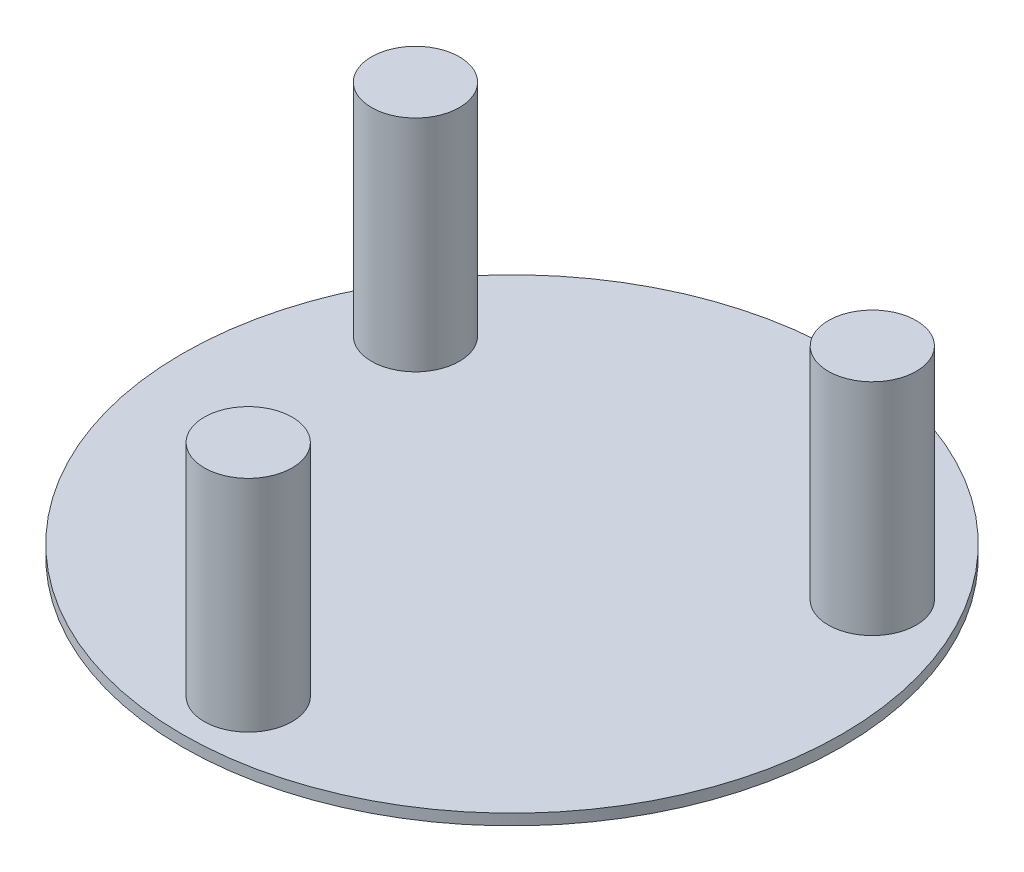
SolidWorks part; units mm, degrees
ref_plane "前视基准面" through (0, 0, 0) normal (0, 0, 1) x (1, 0, 0)
ref_plane "上视基准面" through (0, 0, 0) normal (0, 1, 0) x (1, 0, 0)
ref_plane "右视基准面" through (0, 0, 0) normal (1, 0, 0) x (0, 0, -1)
sketch "草图1" plane through (0, 0, 0) normal (0, 1, 0) x (1, 0, 0)
  circle A0 centre (0, 0) radius 150
  dimension "D1" = 300
extrude "凸台-拉伸1" add sketch "草图1" along normal blind 5
sketch "草图2" plane through (0, 5, 0) normal (0, 1, 0) x (1, 0, 0)
  circle A0 centre (0, 0) radius 120 construction
  circle A1 centre (0, -120) radius 20
  dimension "D1" = 240
  dimension "D2" = 40
extrude "凸台-拉伸2" add sketch "草图2" along normal blind 100
pattern_circular "阵列(圆周)1" count 3 over 360 about axis through (0, 0, 0) along (0, 1, 0) of "凸台-拉伸2"
sketch "草图3" plane through (0, 0, 0) normal (0, -1, 0) x (1, 0, 0)
  circle A0 centre (0, 0) radius 2.5
  dimension "D1" = 5
extrude "凸台-拉伸3" add sketch "草图3" along normal blind 15
